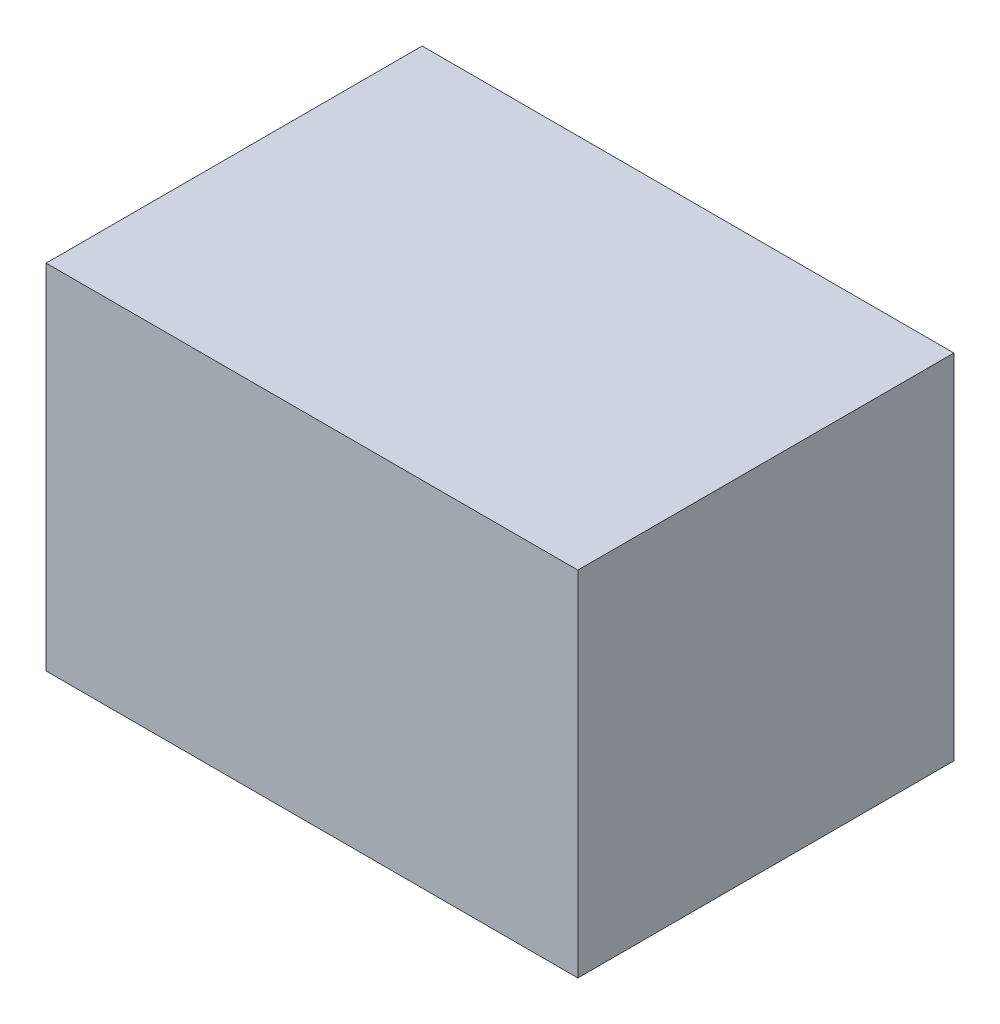
SolidWorks part; units mm, degrees
material "1023 Carbon Steel Sheet (SS)"
ref_plane "Front Plane" through (0, 0, 0) normal (0, 0, 1) x (1, 0, 0)
ref_plane "Top Plane" through (0, 0, 0) normal (0, 1, 0) x (1, 0, 0)
ref_plane "Right Plane" through (0, 0, 0) normal (1, 0, 0) x (0, 0, -1)
sketch "Sketch1" plane through (0, 0, 0) normal (0, 1, 0) x (1, 0, 0)
  line L1 (-712.0843, 271.9518) -> (-432.0843, 271.9518)
  line L2 (-712.0843, 271.9518) -> (-712.0843, 73.9518)
  line L3 (-712.0843, 73.9518) -> (-432.0843, 73.9518)
  line L4 (-432.0843, 271.9518) -> (-432.0843, 73.9518)
  dimension "D1" = 198
  dimension "D2" = 280
extrude "Boss-Extrude1" add sketch "Sketch1" along normal blind 186
